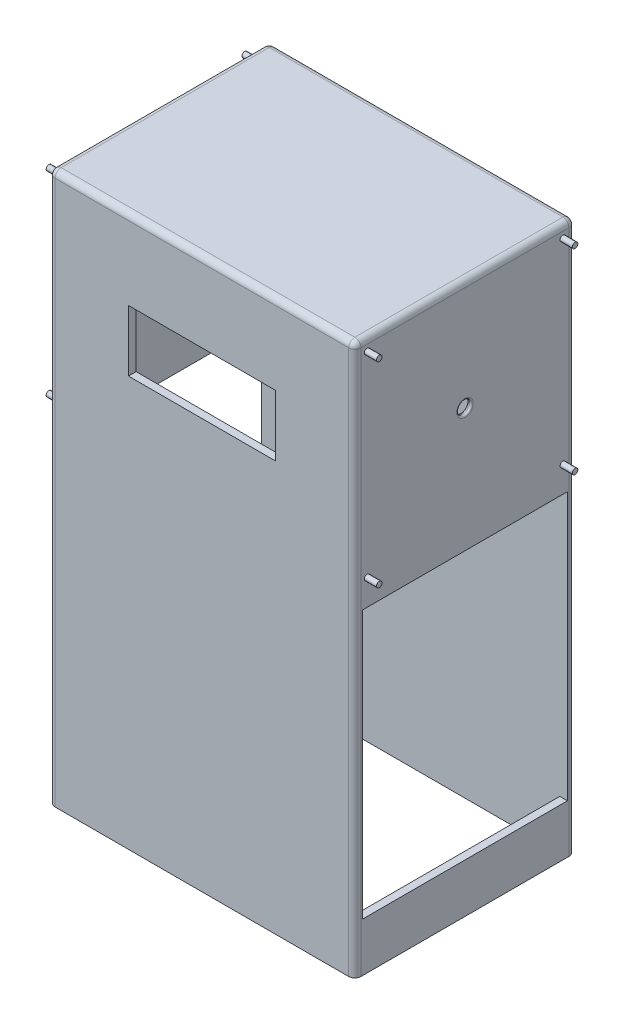
SolidWorks part; units mm, degrees
ref_plane "Front Plane" through (0, 0, 0) normal (0, 0, 1) x (1, 0, 0)
ref_plane "Top Plane" through (0, 0, 0) normal (0, 1, 0) x (1, 0, 0)
ref_plane "Right Plane" through (0, 0, 0) normal (1, 0, 0) x (0, 0, -1)
sketch "Sketch1" plane through (0, 0, 0) normal (0, 1, 0) x (1, 0, 0)
  line L1 (-63.5, -45.72) -> (63.5, -45.72)
  line L2 (-63.5, -45.72) -> (-63.5, 45.72)
  line L3 (-63.5, 45.72) -> (63.5, 45.72)
  line L4 (63.5, -45.72) -> (63.5, 45.72)
  line L5 (-63.5, -45.72) -> (63.5, 45.72) construction
  line L6 (-63.5, 45.72) -> (63.5, -45.72) construction
  point P0 (0, 0)
  dimension "D1" = 91.44
  dimension "D2" = 127
extrude "Boss-Extrude1" add sketch "Sketch1" along normal blind 228.6
sketch "Sketch2" plane through (63.5, 0, 0) normal (1, 0, 0) x (0, 0, -1)
  line L1 (-45.72, 137.16) -> (45.72, 137.16) construction
  line L2 (-45.72, 137.16) -> (-45.72, 228.6) construction
  line L3 (-45.72, 228.6) -> (45.72, 228.6) construction
  line L4 (45.72, 137.16) -> (45.72, 228.6) construction
  line L5 (-45.72, 137.16) -> (45.72, 228.6) construction
  line L6 (-45.72, 228.6) -> (45.72, 137.16) construction
  circle A0 centre (0, 182.88) radius 2.667
  point P0 (0, 182.88)
  dimension "D2" = 5.334
  dimension "D1" = 91.44
sketch "Sketch3" plane through (0, 0, 0) normal (0, -1, 0) x (1, 0, 0)
  line L0 (63.5, 45.72) -> (63.5, -45.72) construction
  line L1 (-60.325, -42.545) -> (60.325, -42.545)
  line L2 (-60.325, -42.545) -> (-60.325, 42.545)
  line L3 (-60.325, 42.545) -> (60.325, 42.545)
  line L4 (60.325, -42.545) -> (60.325, 42.545)
  line L5 (-60.325, -42.545) -> (60.325, 42.545) construction
  line L6 (-60.325, 42.545) -> (60.325, -42.545) construction
  line L7 (-63.5, 45.72) -> (63.5, 45.72) construction
  point P0 (0, 0)
  dimension "D1" = 3.175
  dimension "D2" = 3.175
extrude "Cut-Extrude1" cut sketch "Sketch3" against normal blind 226.06
extrude "Cut-Extrude2" cut sketch "Sketch2" against normal through all contours A0
sketch "Sketch4" plane through (63.5, 0, 0) normal (1, 0, 0) x (0, 0, -1)
  line L3 (-45.72, 228.6) -> (45.72, 228.6) construction
  circle A0 centre (-40.64, 223.52) radius 1.143
  circle A1 centre (40.64, 223.52) radius 1.143
  circle A2 centre (40.64, 142.24) radius 1.143
  circle A3 centre (-40.64, 142.24) radius 1.143
  point P0 (0, 182.88)
  dimension "D7" = 2.286
extrude "Boss-Extrude3" add sketch "Sketch4" along normal blind 5.08
sketch "Sketch5" plane through (60.325, 0, 0) normal (-1, 0, 0) x (0, 0, 1)
  circle A0 centre (0, 182.88) radius 20.32
  dimension "D1" = 40.64
extrude "Cut-Extrude3" cut sketch "Sketch5" against normal blind 1.27
fillet "Fillet1" radius 0.762 1 edges at (61.595, 182.88, 2.667)
fillet "Fillet2" radius 0.762 1 edges at (63.5, 182.88, -2.667)
sketch "Sketch6" plane through (0, 0, 45.72) normal (0, 0, 1) x (1, 0, 0)
  line L0 (0, 0) -> (0, 228.6) construction
  line L1 (-63.5, 228.6) -> (63.5, 228.6) construction
  line L3 (2.7526, 228.6) -> (2.7526, 182.88) construction
  line L4 (-30.48, 170.18) -> (30.48, 170.18)
  line L5 (30.48, 170.18) -> (30.48, 195.58)
  line L6 (-30.48, 170.18) -> (-30.48, 195.58)
  line L7 (30.48, 195.58) -> (-30.48, 195.58)
  line L8 (-30.48, 182.88) -> (30.48, 182.88) construction
  point P10 (0, 170.18)
  dimension "D1" = 45.72
  dimension "D2" = 60.96
  dimension "D3" = 25.4
mirror "Mirror2" about plane through (0, 0, 0) normal (1, 0, 0) of "Cut-Extrude3", "Boss-Extrude3"
fillet "Fillet3" radius 0.762 2 edges at (-61.595, 182.88, -2.667) (-63.5, 182.88, -2.667)
extrude "Cut-Extrude4" cut sketch "Sketch6" against normal through all
fillet "Fillet4" radius 2.54 8 edges at (63.5, 228.6, 0) (0, 228.6, 45.72) (0, 228.6, -45.72) (-63.5, 228.6, 0) (-63.5, 114.3, -45.72) (-63.5, 114.3, 45.72) (63.5, 114.3, 45.72) (63.5, 114.3, -45.72)
sketch "Sketch7" plane through (63.5, 0, 0) normal (1, 0, 0) x (0, 0, -1)
  line L0 (45.72, 226.06) -> (45.72, 0) construction
  line L1 (-42.545, 20.32) -> (42.545, 20.32)
  line L2 (-42.545, 20.32) -> (-42.545, 131.4726)
  line L3 (-42.545, 131.4726) -> (42.545, 131.4726)
  line L4 (42.545, 20.32) -> (42.545, 131.4726)
  line L5 (-42.545, 20.32) -> (42.545, 131.4726) construction
  line L6 (-42.545, 131.4726) -> (42.545, 20.32) construction
  line L7 (-45.72, 0) -> (-45.72, 226.06) construction
  line L8 (-43.18, 0) -> (43.18, 0) construction
  point P0 (0, 75.8963)
  dimension "D1" = 3.175
  dimension "D2" = 3.175
  dimension "D3" = 20.32
extrude "Cut-Extrude5" cut sketch "Sketch7" against normal through all
sketch "Sketch8" plane through (0, 0, 0) normal (0, 1, 0) x (1, 0, 0)
  line L0 (0, 0) -> (-63.5, 0)
  line L1 (-63.5, 43.18) -> (-63.5, -43.18) construction
  line L2 (-49.2123, 0) -> (-49.2123, 45.72)
  line L3 (-45.2134, 0) -> (-45.2134, 15.24)
  line L4 (60.96, 45.72) -> (-60.96, 45.72) construction
  line L5 (-60.325, 29.0103) -> (-34.925, 29.0103)
  line L6 (-60.325, -42.545) -> (-60.325, 42.545) construction
  dimension "D1" = 45.72
  dimension "D2" = 15.24
  dimension "D3" = 30.48
  dimension "D4" = 25.4
